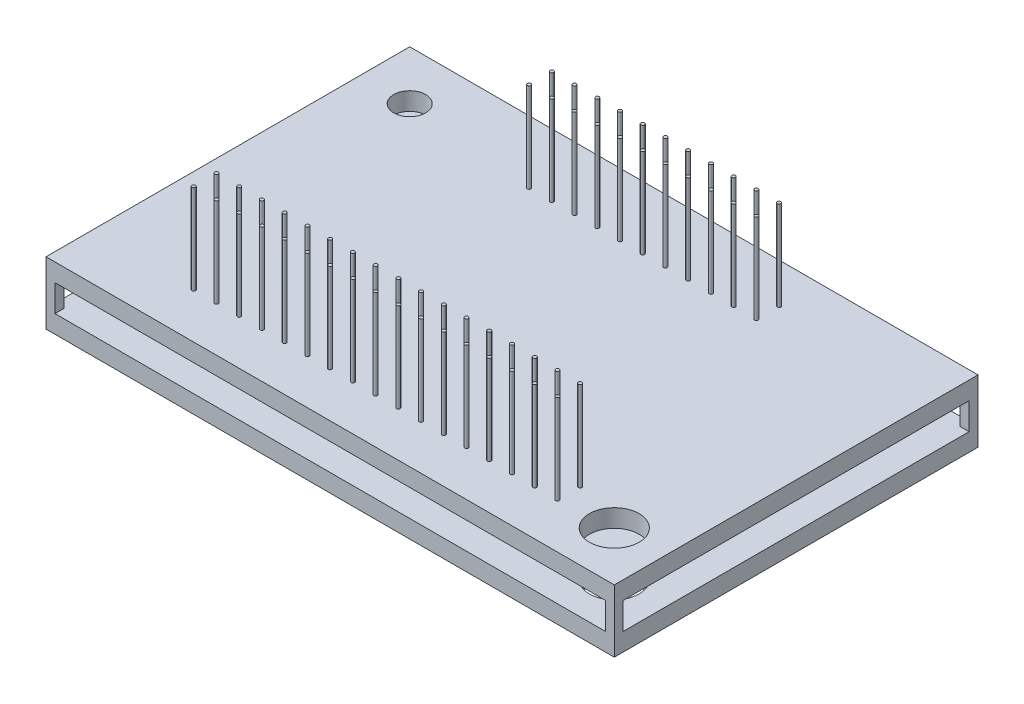
SolidWorks part; units mm, degrees
ref_plane "前视基准面" through (0, 0, 0) normal (0, 0, 1) x (1, 0, 0)
ref_plane "上视基准面" through (0, 0, 0) normal (0, 1, 0) x (1, 0, 0)
ref_plane "右视基准面" through (0, 0, 0) normal (1, 0, 0) x (0, 0, -1)
sketch "草图1" plane through (0, 0, 0) normal (0, 1, 0) x (1, 0, 0)
  line L1 (-31.75, -20.32) -> (31.75, -20.32)
  line L2 (-31.75, -20.32) -> (-31.75, 20.32)
  line L3 (-31.75, 20.32) -> (31.75, 20.32)
  line L4 (31.75, -20.32) -> (31.75, 20.32)
  line L5 (-31.75, -20.32) -> (31.75, 20.32) construction
  line L6 (-31.75, 20.32) -> (31.75, -20.32) construction
  point P0 (0, 0)
  dimension "D1" = 63.5
  dimension "D2" = 40.64
extrude "凸台-拉伸1" add sketch "草图1" along normal blind 7
sketch "草图2" plane through (0, 0, -20.32) normal (0, 0, -1) x (-1, 0, 0)
  line L0 (31.75, 7) -> (31.75, 0) construction
  line L1 (30.75, 5) -> (-30.75, 5)
  line L2 (30.75, 5) -> (30.75, 2)
  line L3 (30.75, 2) -> (-30.75, 2)
  line L4 (-30.75, 5) -> (-30.75, 2)
  line L5 (-31.75, 7) -> (31.75, 7) construction
  line L6 (-31.75, 0) -> (31.75, 0) construction
  line L7 (-31.75, 7) -> (-31.75, 0) construction
  dimension "D1" = 1
  dimension "D2" = 2
  dimension "D3" = 2
  dimension "D4" = 1
extrude "切除-拉伸1" cut sketch "草图2" against normal up to next
sketch "草图3" plane through (-31.75, 0, 0) normal (-1, 0, 0) x (0, 0, 1)
  line L0 (-20.32, 0) -> (20.32, 0) construction
  line L1 (19.32, 5) -> (-19.32, 5)
  line L2 (19.32, 5) -> (19.32, 2)
  line L3 (19.32, 2) -> (-19.32, 2)
  line L4 (-19.32, 5) -> (-19.32, 2)
  line L5 (20.32, 7) -> (20.32, 0) construction
  line L6 (-20.32, 7) -> (20.32, 7) construction
  line L7 (-20.32, 7) -> (-20.32, 0) construction
  point P6 (20.32, 3.5)
  dimension "D1" = 2
  dimension "D2" = 1
  dimension "D3" = 2
  dimension "D4" = 1
extrude "切除-拉伸2" cut sketch "草图3" against normal through all
sketch "草图4" plane through (0, 7, 0) normal (0, 1, 0) x (1, 0, 0)
  line L0 (-31.75, -20.32) -> (31.75, -20.32) construction
  line L1 (-31.75, 20.32) -> (-31.75, -20.32) construction
  circle A0 centre (-20.32, -15.24) radius 0.2
  dimension "D1" = 0.4
  dimension "D2" = 5.08
  dimension "D3" = 11.43
extrude "凸台-拉伸2" add sketch "草图4" along normal blind 10
pattern_linear "阵列(线性)1" count 2 spacing 2.54 along (0, 0, -1) of "凸台-拉伸2"
pattern_linear "阵列(线性)2" count 17 spacing 2.54 along (1, 0, 0) of "阵列(线性)1", "凸台-拉伸2"
sketch "草图5" plane through (0, 7, 0) normal (0, 1, 0) x (1, 0, 0)
  circle A0 centre (-11.43, 13.34) radius 0.2
  circle A1 centre (-20.32, -15.24) radius 0.2 construction
  dimension "D1" = 0.4
  dimension "D2" = 8.89
  dimension "D3" = 28.58
extrude "凸台-拉伸3" add sketch "草图5" along normal blind 10
pattern_linear "阵列(线性)3" count 2 spacing 2.54 along (0, 0, -1) of "凸台-拉伸3"
pattern_linear "阵列(线性)4" count 11 spacing 2.54 along (1, 0, 0) of "阵列(线性)3", "凸台-拉伸3"
sketch "草图6" plane through (0, 7, 0) normal (0, 1, 0) x (1, 0, 0)
  circle A0 centre (-26.24, 14.81) radius 1.7822
  circle A1 centre (-20.32, -15.24) radius 0.2 construction
  circle A2 centre (26.24, -14.81) radius 2.7744
  dimension "D1" = 5.92
  dimension "D2" = 30.05
  dimension "D3" = 46.56
  dimension "D4" = 0.43
extrude "切除-拉伸3" cut sketch "草图6" against normal through all
sketch "草图7" plane through (0, 0, 0) normal (0, -1, 0) x (-1, 0, 0)
  text T0 "ACK_055_06"
sketch "草图8" plane through (0, 0, 0) normal (0, -1, 0) x (-1, 0, 0)
  circle A0 centre (-0.7662, 13.5162) radius 2.5
  dimension "D1" = 5
extrude "凸台-拉伸5" add sketch "草图8" along normal blind 10
